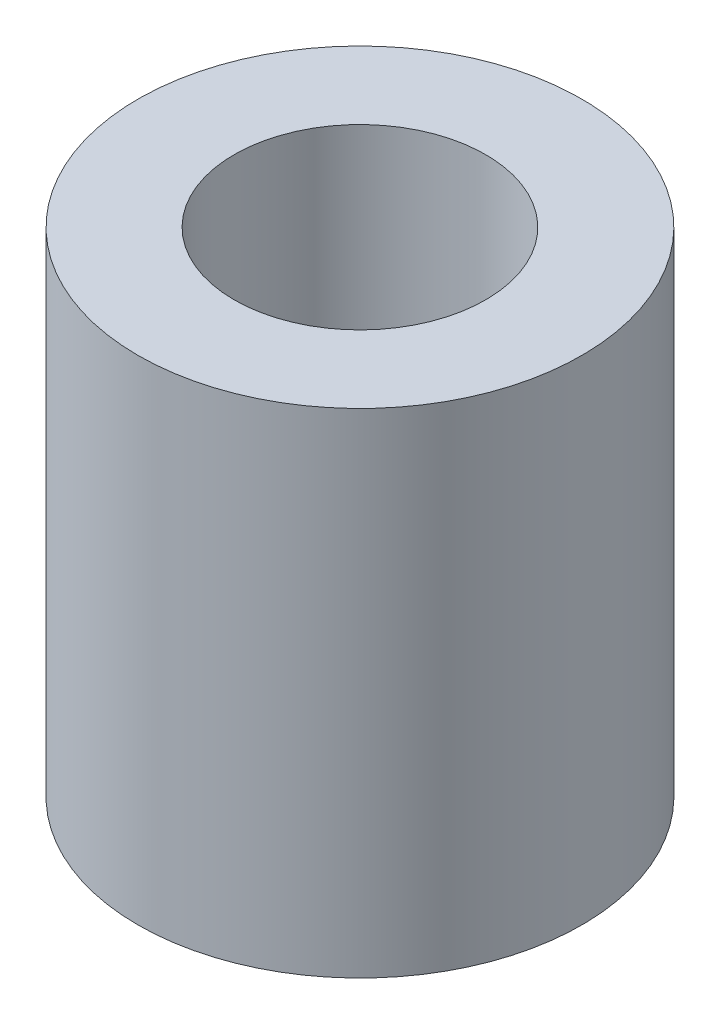
SolidWorks part; units mm, degrees
ref_plane "Front Plane" through (0, 0, 0) normal (0, 0, 1) x (1, 0, 0)
ref_plane "Top Plane" through (0, 0, 0) normal (0, 1, 0) x (1, 0, 0)
ref_plane "Right Plane" through (0, 0, 0) normal (1, 0, 0) x (0, 0, -1)
sketch "Sketch1" plane through (0, 0, 0) normal (0, 1, 0) x (1, 0, 0)
  circle A0 centre (0, 0) radius 4.5
  circle A1 centre (0, 0) radius 2.55
  dimension "D1" = 9
  dimension "D2" = 5.1
extrude "Boss-Extrude1" add sketch "Sketch1" along normal blind 10
